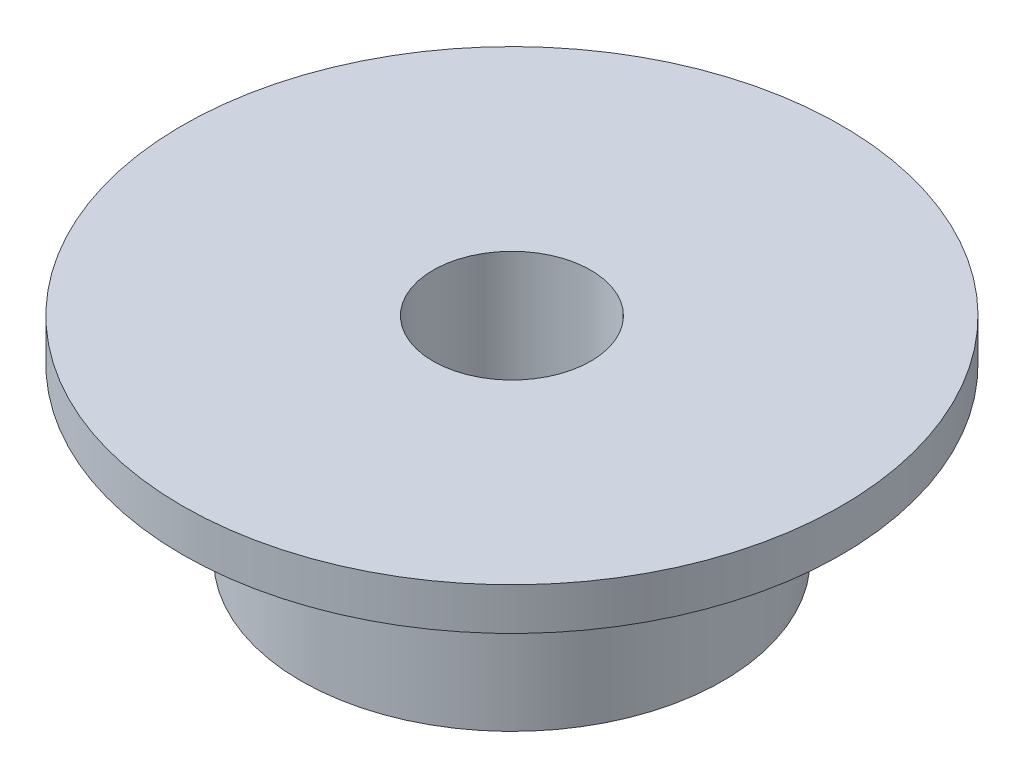
SolidWorks part; units mm, degrees
ref_plane "Front Plane" through (0, 0, 0) normal (0, 0, 1) x (1, 0, 0)
ref_plane "Top Plane" through (0, 0, 0) normal (0, 1, 0) x (1, 0, 0)
ref_plane "Right Plane" through (0, 0, 0) normal (1, 0, 0) x (0, 0, -1)
sketch "Sketch1" plane through (0, 0, 0) normal (0, 1, 0) x (1, 0, 0)
  circle A0 centre (-17.6074, 10.4109) radius 12.7
  dimension "D1" = 25.4
extrude "Boss-Extrude1" add sketch "Sketch1" along normal blind 10.16
sketch "Sketch2" plane through (0, 10.16, 0) normal (0, 1, 0) x (1, 0, 0)
  circle A0 centre (-17.6074, 10.4109) radius 4.7498
  circle A1 centre (-17.6074, 10.4109) radius 19.8438
  dimension "D1" = 9.4996
  dimension "D2" = 39.6875
extrude "Boss-Extrude2" add sketch "Sketch2" along normal blind 2.54
sketch "Sketch3" plane through (0, 10.16, 0) normal (0, 1, 0) x (1, 0, 0)
  circle A0 centre (-17.6074, 10.4109) radius 4.7498
extrude "Cut-Extrude1" cut sketch "Sketch3" against normal blind 12.7
